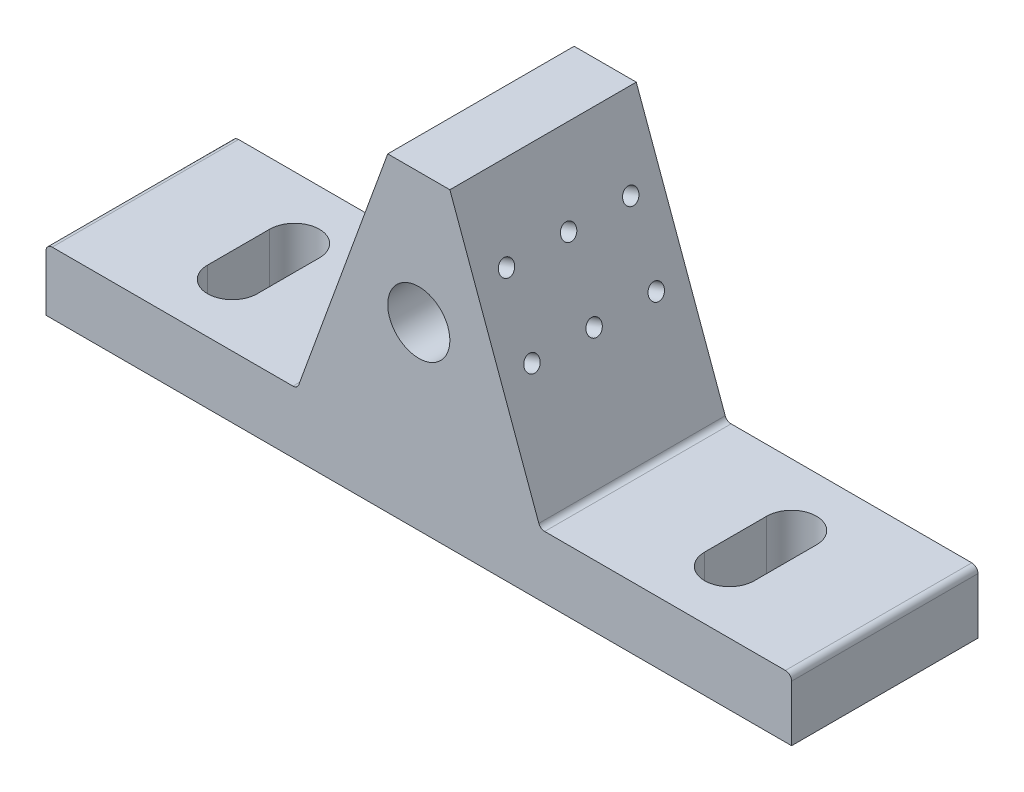
SolidWorks part; units mm, degrees
material "AISI 304"
ref_plane "Front Plane" through (0, 0, 0) normal (0, 0, 1) x (1, 0, 0)
ref_plane "Top Plane" through (0, 0, 0) normal (0, 1, 0) x (1, 0, 0)
ref_plane "Right Plane" through (0, 0, 0) normal (1, 0, 0) x (0, 0, -1)
sketch "Sketch1" plane through (0, 0, 0) normal (0, 0, 1) x (1, 0, 0)
  line L0 (0, 0) -> (0, 50) construction
  line L1 (-60, 0) -> (60, 0)
  line L2 (60, 0) -> (60, 10)
  line L3 (-60, 0) -> (-60, 10)
  line L4 (60, 10) -> (19.5588, 10)
  line L5 (-60, 10) -> (-19.5588, 10)
  line L6 (19.5588, 10) -> (5, 50)
  line L7 (-19.5588, 10) -> (-5, 50)
  line L8 (5, 50) -> (-5, 50)
  dimension "D1" = 110
  dimension "D2" = 10
  dimension "D3" = 50
  dimension "D4" = 10
  dimension "D5" = 120
extrude "Base Extrude" add sketch "Sketch1" along normal mid plane 30
sketch "Sketch2" plane through (0, 10, 0) normal (0, 1, 0) x (1, 0, 0)
  line L0 (40, -5) -> (40, 5) construction
  line L1 (36, -5) -> (36, 5)
  line L2 (44, -5) -> (44, 5)
  line L3 (60, 15) -> (19.5588, 15) construction
  arc A0 (36, -5) -> (44, -5) centre (40, -5) ccw
  arc A1 (44, 5) -> (36, 5) centre (40, 5) ccw
  point P2 (40, 0)
  dimension "D4" = 4
  dimension "D1" = 40
  dimension "D2" = 10
  dimension "D3" = 10
extrude "Slot Cut" cut sketch "Sketch2" against normal through all
mirror "Mirror1" about plane through (0, 0, 0) normal (1, 0, 0) of "Slot Cut"
sketch "Sketch3" plane through (0, 0, 15) normal (0, 0, 1) x (1, 0, 0)
  circle A0 centre (0, 29) radius 5
  dimension "D1" = 10
  dimension "D2" = 29
extrude "Guide hole" cut sketch "Sketch3" against normal through all
hole_wizard "M3x0.5 Tapped Hole3" positions "Sketch11" profile "Sketch10" tap size "M3x0.5" standard "ANSI Metric"
sketch "Sketch11" plane through (20.4848, 7.4559, 0) normal (0.9397, 0.342, 0) x (0, 0, -1)
  line L0 (15, 2.7074) -> (15, 45.2745) construction
  line L1 (15, 27.2511) -> (-15, 27.2511) construction
  point P0 (-10, 21.2511)
  dimension "D1" = 25
  dimension "D2" = 6
sketch "Sketch10" plane through (13.2165, 27.4253, 10) normal (0, 0, 1) x (-0.342, 0.9397, 0)
  line L0 (0, 0) -> (0, 8.2511)
  line L1 (0, 8.2511) -> (1.25, 7.5)
  line L2 (1.25, 7.5) -> (1.25, 0)
  line L5 (1.25, 0) -> (0, 0)
  line L10 (0, 8.2511) -> (-1.25, 7.5) construction
  line L11 (0, -6.35) -> (0, 107.95) construction
  dimension "Tap Drill Dia." = 2.5
  dimension "Tap Drill Depth" = 7.5
  dimension "Drill Angle" = 118
cosmetic thread "Hole Thread1" parameters "D1"=6, "D2"=3
pattern_linear "LPattern1" count 3 spacing 10 along (0, 0, -1) count 2 spacing 12 along (-0.342, 0.9397, 0) of "M3x0.5 Tapped Hole3"
fillet "Fillet1" radius 1 4 edges at (-19.5588, 10, 0) (-60, 10, 0) (60, 10, 0) (19.5588, 10, 0)
